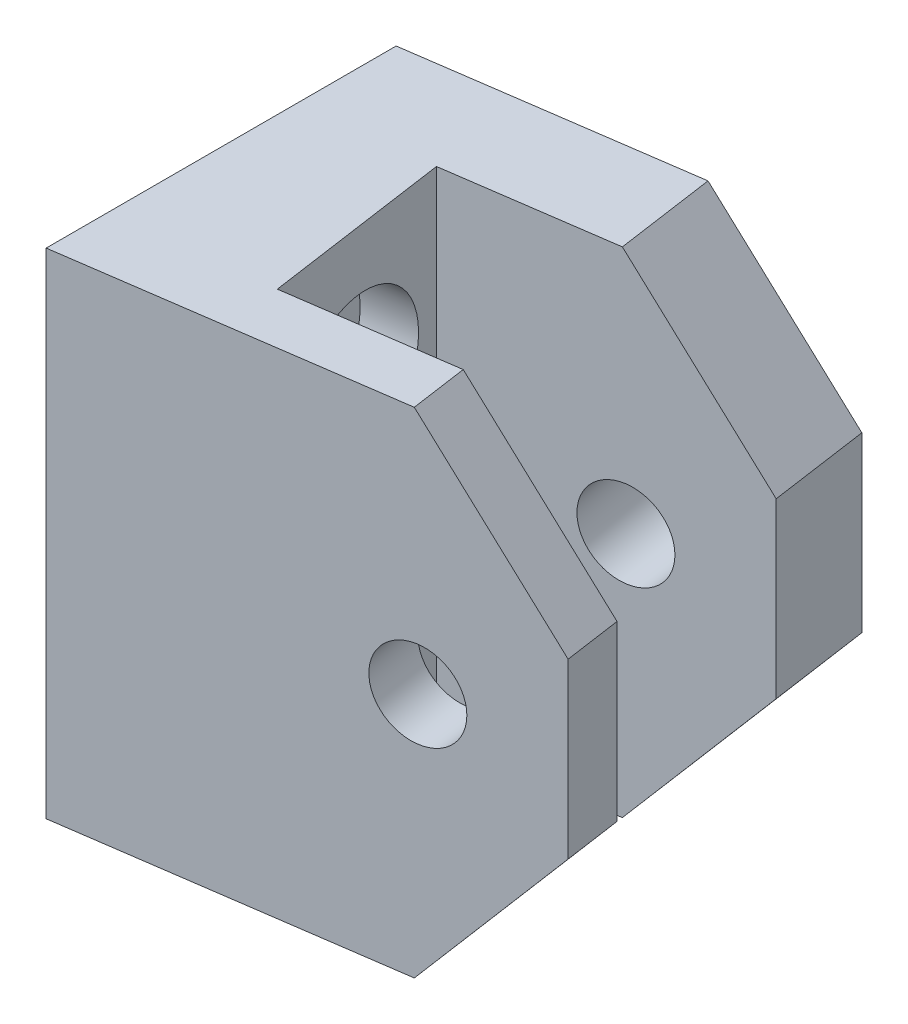
SolidWorks part; units mm, degrees
material "6061-T6 (SS)"
ref_plane "X-Y Datum" through (0, 0, 0) normal (0, 0, 1) x (1, 0, 0)
ref_plane "X-Z Datum" through (0, 0, 0) normal (0, 1, 0) x (1, 0, 0)
ref_plane "Y-Z Datum" through (0, 0, 0) normal (1, 0, 0) x (0, 0, -1)
sketch "Sketch1" plane through (0, 0, 0) normal (0, 1, 0) x (1, 0, 0)
  line L10 (42.9004, 10.9664) -> (-1.905, 4.5379)
  line L11 (31.488, -12.3281) -> (6.9122, -15.8541) construction
  line L12 (31.488, -12.3281) -> (37.2397, -52.4164) construction
  line L13 (47.4113, -20.4743) -> (14.7261, -25.1639)
  line L14 (14.7261, -25.1639) -> (11.7933, -4.723)
  line L15 (11.7933, -4.723) -> (44.4786, -0.0334)
  line L16 (47.4113, -20.4743) -> (48.3132, -26.7599)
  line L17 (48.3132, -26.7599) -> (-0.0216, -33.6948)
  line L19 (44.4786, -0.0334) -> (42.9004, 10.9664)
  line L24 (-1.905, 4.5379) -> (-1.905, -33.8451)
  line L25 (-0.0216, -33.6948) -> (-1.905, -33.965)
  line L26 (-1.905, -33.965) -> (-1.905, -33.8451)
  line L27 (-1.905, 4.5379) -> (-1.905, 90.7516) construction
  line L28 (11.7933, -4.723) -> (-1.905, 90.7516) construction
  point P0 (31.488, -12.3281)
  point P3 (0, 0)
  point P14 (0, 0)
  point P15 (0, 0)
  point P19 (124.5011, 2.3164)
  point P20 (0, 0)
  dimension "D1" = 18.415
  dimension "D2" = 33.393
  dimension "D3" = 50.7324
  dimension "D4" = 8.165
  dimension "D5" = 10.3251
  dimension "D6" = 10.3251
  dimension "D7" = 14.605
  dimension "D8" = 6.35
  dimension "D9" = 11.1125
  dimension "D10" = 21.517
extrude "Boss-Extrude1" add sketch "Sketch1" along normal blind 54.3789
sketch "Sketch6" plane through (4.7364, 0, 33.0121) normal (0.142, 0, 0.9899) x (0.9899, 0, -0.142)
  line L0 (-6.7095, 54.3789) -> (44.023, 54.3789) construction
  line L1 (44.023, 36.7144) -> (29.0719, 54.3789)
  line L2 (44.023, 54.3789) -> (44.023, 0) construction
  line L3 (29.0719, 54.3789) -> (44.023, 54.3789)
  line L4 (44.023, 54.3789) -> (44.023, 36.7144)
  line L5 (29.418, 27.1894) -> (40.6527, 27.1894) construction
  line L6 (44.023, 0) -> (44.023, 17.6644)
  line L7 (29.0719, 0) -> (44.023, 0)
  line L8 (44.023, 17.6644) -> (29.0719, 0)
  circle A0 centre (29.418, 27.1894) radius 4.7625
  dimension "D1" = 9.525
  dimension "D2" = 27.1894
  dimension "D3" = 19.05
extrude "Cut-Extrude2" cut sketch "Sketch6" against normal through all
sketch "Sketch16" plane through (10.8914, 0, -1.5627) normal (0.9899, 0, -0.142) x (-0.142, 0, -0.9899)
  line L0 (-27.0002, 27.1894) -> (-6.35, 27.1894) construction
  line L1 (-16.6751, 54.3789) -> (-16.6751, 0) construction
  line L4 (-27.0002, 0) -> (-6.35, 0)
  line L5 (-6.35, 0) -> (-6.35, 54.3789)
  line L6 (-6.35, 54.3789) -> (-27.0002, 54.3789)
  line L7 (-27.0002, 54.3789) -> (-27.0002, 0)
  line L8 (-27.0002, 0) -> (-6.35, 0) construction
  line L9 (-6.35, 0) -> (-6.35, 54.3789) construction
  line L10 (-6.35, 54.3789) -> (-27.0002, 54.3789) construction
  line L11 (-27.0002, 54.3789) -> (-27.0002, 0) construction
  point P8 (-16.6751, 14.4894)
  point P9 (-16.6751, 39.8894)
  dimension "D2" = 12.7
  dimension "D3" = 25.4
  dimension "D1" = 0
hole_wizard "CBORE for M8 Hex Head Bolt1" positions "Sketch17" profile "Sketch18" counterbore size "M8" standard "ANSI Metric" end condition through all
sketch "Sketch17" plane through (10.8914, 0, -1.5627) normal (0.9899, 0, -0.142) x (-0.142, 0, -0.9899)
  point P0 (-16.6751, 39.8894)
  point P3 (-16.6751, 14.4894)
sketch "Sketch18" plane through (13.2597, 39.8894, 14.9434) normal (0, 1, 0) x (-0.142, 0, -0.9899)
  line L0 (0, 0) -> (0, 17.7124)
  line L1 (0, 17.7124) -> (4.5, 17.7124)
  line L3 (4.5, 17.7124) -> (4.5, 5.68)
  line L4 (4.5, 5.68) -> (8, 5.68)
  line L5 (8, 5.68) -> (8, 0)
  line L7 (8, 0) -> (0, 0)
  line L11 (0, -6.35) -> (0, 107.95) construction
  dimension "Thru Hole Dia." = 9
  dimension "Thru Hole Depth" = 17.7124
  dimension "C'Bore Dia." = 16
  dimension "C'Bore Depth" = 5.68
